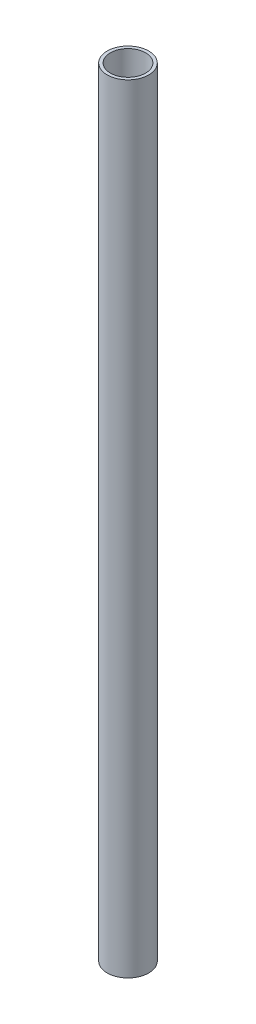
SolidWorks part; units mm, degrees
ref_plane "前视基准面" through (0, 0, 0) normal (0, 0, 1) x (1, 0, 0)
ref_plane "上视基准面" through (0, 0, 0) normal (0, 1, 0) x (1, 0, 0)
ref_plane "右视基准面" through (0, 0, 0) normal (1, 0, 0) x (0, 0, -1)
other "Configuration Table"
sketch "草图1" plane through (0, 0, 0) normal (0, 1, 0) x (1, 0, 0)
  circle A14 centre (0, 0) radius 16
  circle A15 centre (0, 0) radius 13.6
  dimension "D1" = 32
  dimension "D2" = 2.4
extrude "凸台-拉伸1" add sketch "草图1" along normal blind 600
